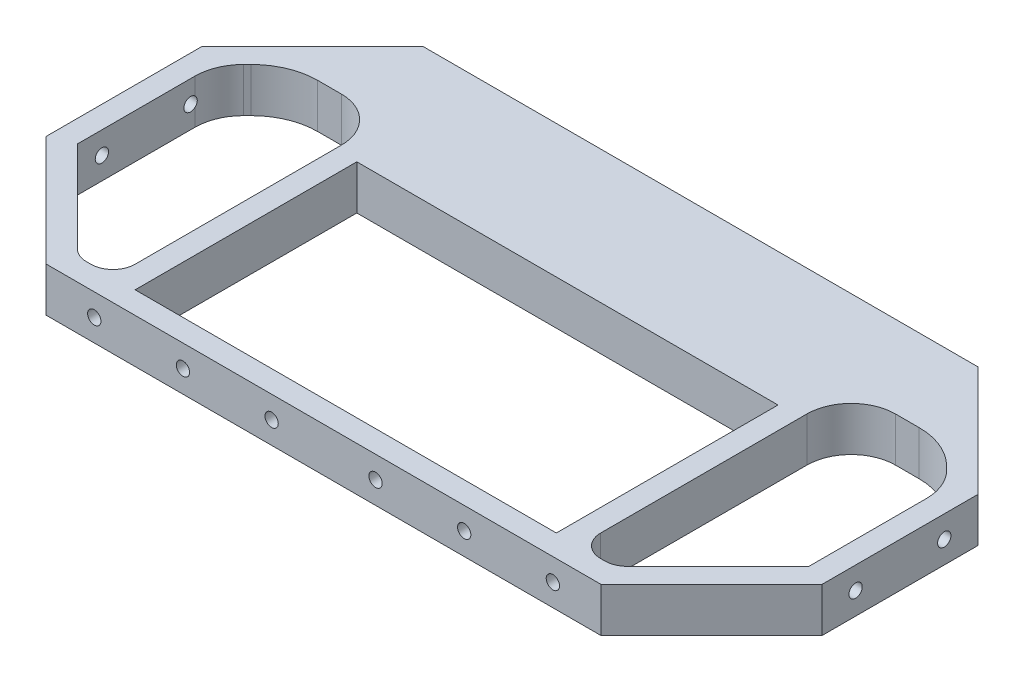
SolidWorks part; units mm, degrees
ref_plane "前视基准面" through (0, 0, 0) normal (0, 0, 1) x (1, 0, 0)
ref_plane "上视基准面" through (0, 0, 0) normal (0, 1, 0) x (1, 0, 0)
ref_plane "右视基准面" through (0, 0, 0) normal (1, 0, 0) x (0, 0, -1)
sketch "草图1" plane through (0, 0, 0) normal (0, 1, 0) x (1, 0, 0)
  line L0 (130, 16.5685) -> (106.5685, 40) construction
  line L2 (16.5685, 40) -> (-16.5685, 40) construction
  line L3 (-16.5685, 40) -> (-40, 16.5685) construction
  line L4 (-40, 16.5685) -> (-40, -16.5685) construction
  line L5 (-40, -16.5685) -> (-16.5685, -40) construction
  line L6 (-16.5685, -40) -> (16.5685, -40) construction
  line L9 (106.5685, 40) -> (73.4315, 40) construction
  line L13 (73.4315, -40) -> (106.5685, -40) construction
  line L14 (106.5685, -40) -> (130, -16.5685) construction
  line L15 (130, -16.5685) -> (130, 16.5685) construction
  line L16 (0, 0) -> (90, 0) construction
  line L17 (16.5685, 40) -> (73.4315, 40) construction
  line L18 (16.5685, -40) -> (73.4315, -40) construction
  line L19 (16.5685, 42.5) -> (73.4315, 42.5)
  line L20 (16.5685, 42.5) -> (-17.6041, 42.5)
  line L21 (-17.6041, 42.5) -> (-42.5, 17.6041)
  line L22 (-42.5, 17.6041) -> (-42.5, -17.6041)
  line L23 (-42.5, -17.6041) -> (-17.6041, -42.5)
  line L24 (-17.6041, -42.5) -> (16.5685, -42.5)
  line L25 (73.4315, -42.5) -> (107.6041, -42.5)
  line L26 (107.6041, -42.5) -> (132.5, -17.6041)
  line L27 (132.5, -17.6041) -> (132.5, 17.6041)
  line L28 (132.5, 17.6041) -> (107.6041, 42.5)
  line L29 (107.6041, 42.5) -> (73.4315, 42.5)
  line L30 (16.5685, -42.5) -> (73.4315, -42.5)
  line L31 (28.2843, 28.2843) -> (16.5685, 40) [skipped]
  line L32 (40, -16.5685) -> (40, 0) [skipped]
  line L33 (16.5685, -40) -> (28.2843, -28.2843) [skipped]
  line L34 (16.5685, 37.5) -> (-15.533, 37.5)
  line L41 (-15.533, 37.5) -> (-37.5, 15.533)
  line L42 (-37.5, 15.533) -> (-37.5, -15.533)
  line L43 (-37.5, -15.533) -> (-15.533, -37.5)
  line L44 (-15.533, -37.5) -> (-7.5, -37.5)
  line L45 (16.5685, -37.5) -> (73.4315, -37.5)
  line L46 (73.4315, -37.5) -> (83.1419, -37.5)
  line L47 (105.533, -37.5) -> (127.5, -15.533)
  line L48 (127.5, -15.533) -> (127.5, 15.533)
  line L49 (127.5, 15.533) -> (105.533, 37.5)
  line L50 (105.533, 37.5) -> (73.4315, 37.5)
  line L51 (16.5685, 37.5) -> (73.4315, 37.5)
  line L52 (-7.5, 24) -> (-29.033, 24)
  line L53 (-2.5, -36) -> (92.5, -36) construction
  line L54 (-2.5, -28) -> (-2.5, 12.5) construction
  line L56 (92.5, -28) -> (92.5, 12.5) construction
  line L57 (-2.5, -36) -> (92.5, 24) construction
  line L58 (-2.5, 24) -> (92.5, -36) construction
  line L59 (97.5, 24) -> (119.033, 24)
  line L60 (-7.5, 24) -> (-7.5, -37.5)
  line L61 (92.5, 12.5) -> (92.5, -28)
  line L62 (6.8581, -37.5) -> (16.5685, -37.5)
  line L63 (-15.533, -37.5) -> (16.5685, -37.5) construction
  line L64 (-2.5, -28) -> (-2.5, 12.5)
  line L65 (97.5, 24) -> (97.5, -37.5)
  line L66 (97.5, -37.5) -> (105.533, -37.5)
  line L67 (73.4315, -37.5) -> (105.533, -37.5) construction
  line L68 (-2.5, -28) -> (-2.5, -37.5)
  line L69 (-2.5, -37.5) -> (6.8581, -37.5)
  line L70 (92.5, -28) -> (92.5, -37.5)
  line L71 (92.5, -37.5) -> (83.1419, -37.5)
  line L76 (-2.5, 12.5) -> (92.5, 12.5)
  arc A0 (0, 40) -> (0, -40) centre (0, 0) ccw construction
  arc A1 (90, -40) -> (90, 40) centre (90, 0) ccw construction
  point P2 (45, 0)
  point P20 (45, -6)
  dimension "D1" = 80
  dimension "D2" = 80
  dimension "D12" = 4
  dimension "D13" = 50
  dimension "D17" = 135
  dimension "D3" = 90
  dimension "D4" = 56.8629
  dimension "D5" = 56.8629
  dimension "D8" = 60
  dimension "D9" = 95
  dimension "D15" = 37.5
  dimension "D6" = 2.5
  dimension "D7" = 2.5
  dimension "D10" = 5
  dimension "D11" = 5
extrude "凸台-拉伸1" add sketch "草图1" along normal blind 10
fillet "圆角1" radius 10 2 edges at (97.5, 5, -24) (-7.5, 5, -24)
fillet "圆角11" radius 5 4 edges at (97.5, 5, 37.5) (-15.533, 5, 37.5) (-7.5, 5, 37.5) (105.533, 5, 37.5)
fillet "圆角21" radius 15 2 edges at (119.033, 5, -24) (-29.033, 5, -24)
fillet "圆角24" radius 11 2 edges at (127.5, 5, -15.533) (-37.5, 5, -15.533)
sketch "草图2" plane through (0, 0, -42.5) normal (0, 0, -1) x (-1, 0, 0)
  line L2 (-107.6041, 5) -> (17.6041, 5) construction
  line L4 (-45, 5) -> (-45, 10) construction
  circle A0 centre (-33.282, 5) radius 1.5
  circle A1 centre (-13.282, 5) radius 1.5
  circle A2 centre (6.718, 5) radius 1.5
  circle A3 centre (-96.718, 5) radius 1.5
  circle A4 centre (-76.718, 5) radius 1.5
  circle A5 centre (-56.718, 5) radius 1.5
  point P10 (-33.282, 10)
  dimension "D2" = 3
sketch "草图3" plane through (132.5, 0, 0) normal (1, 0, 0) x (0, 0, -1)
  line L1 (0, 10) -> (0, 0) construction
  line L4 (-17.1361, 5) -> (18.072, 5) construction
  circle A0 centre (10, 5) radius 1.5
  circle A1 centre (-10, 5) radius 1.5
  dimension "D1" = 10
sketch "草图4" plane through (0, 0, 42.5) normal (0, 0, 1) x (1, 0, 0)
  circle A0 centre (56.718, 5) radius 1.5
  circle A1 centre (76.718, 5) radius 1.5
  circle A2 centre (96.718, 5) radius 1.5
  circle A3 centre (33.282, 5) radius 1.5
  circle A4 centre (13.282, 5) radius 1.5
  circle A5 centre (-6.718, 5) radius 1.5
  dimension "D1" = 3
  dimension "D2" = 3
sketch "草图5" plane through (-42.5, 0, 0) normal (-1, 0, 0) x (0, 0, 1)
  circle A0 centre (10, 5) radius 1.5
  circle A1 centre (-10, 5) radius 1.5
extrude "切除-拉伸1" cut sketch "草图5" against normal blind 6
extrude "切除-拉伸2" cut sketch "草图2" against normal blind 6
extrude "切除-拉伸3" cut sketch "草图3" against normal blind 6
extrude "切除-拉伸4" cut sketch "草图4" against normal blind 6
